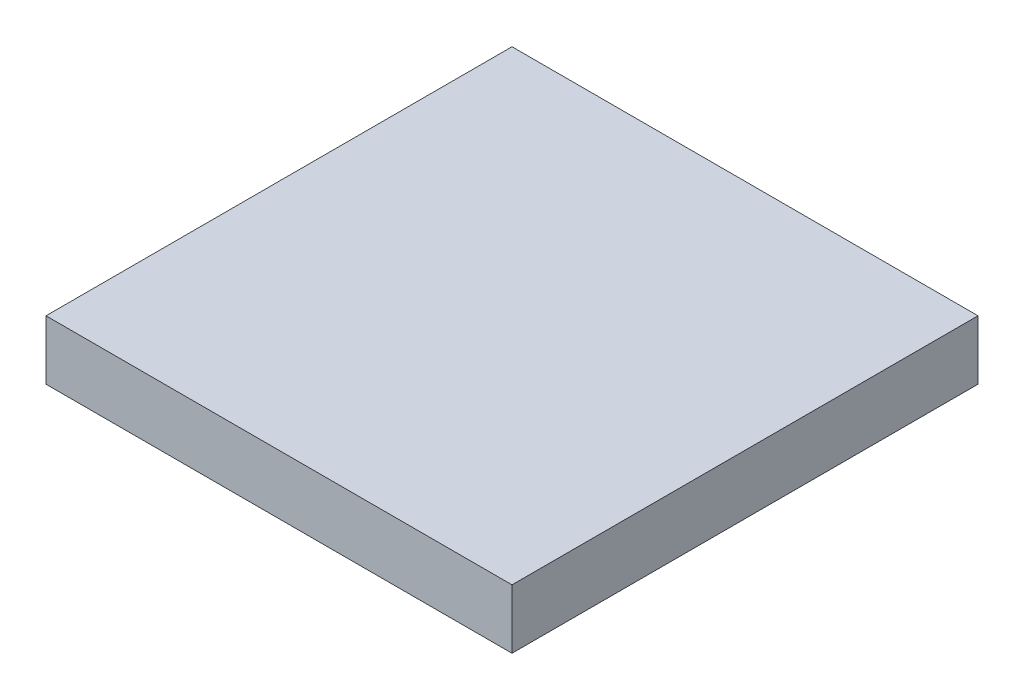
SolidWorks part; units mm, degrees
ref_plane "Front Plane" through (0, 0, 0) normal (0, 0, 1) x (1, 0, 0)
ref_plane "Top Plane" through (0, 0, 0) normal (0, 1, 0) x (1, 0, 0)
ref_plane "Right Plane" through (0, 0, 0) normal (1, 0, 0) x (0, 0, -1)
sketch "Sketch1" plane through (0, 0, 0) normal (0, 1, 0) x (1, 0, 0)
  line L1 (0, 0) -> (50, 0)
  line L2 (0, 0) -> (0, 50)
  line L3 (0, 50) -> (50, 50)
  line L4 (50, 0) -> (50, 50)
  dimension "D1" = 50
  dimension "D2" = 50
extrude "Boss-Extrude1" add sketch "Sketch1" along normal blind 6.36
sketch "Sketch2" plane through (0, 0, 0) normal (0, -1, 0) x (-1, 0, 0)
  line L0 (-25, 0) -> (-25, 50)
  line L1 (0, 0) -> (-50, 0) construction
  line L2 (-50, 50) -> (0, 50) construction
  line L3 (0, 50) -> (0, 0) construction
  line L5 (-50, 0) -> (-50, 50) construction
  point P6 (0, 0)
